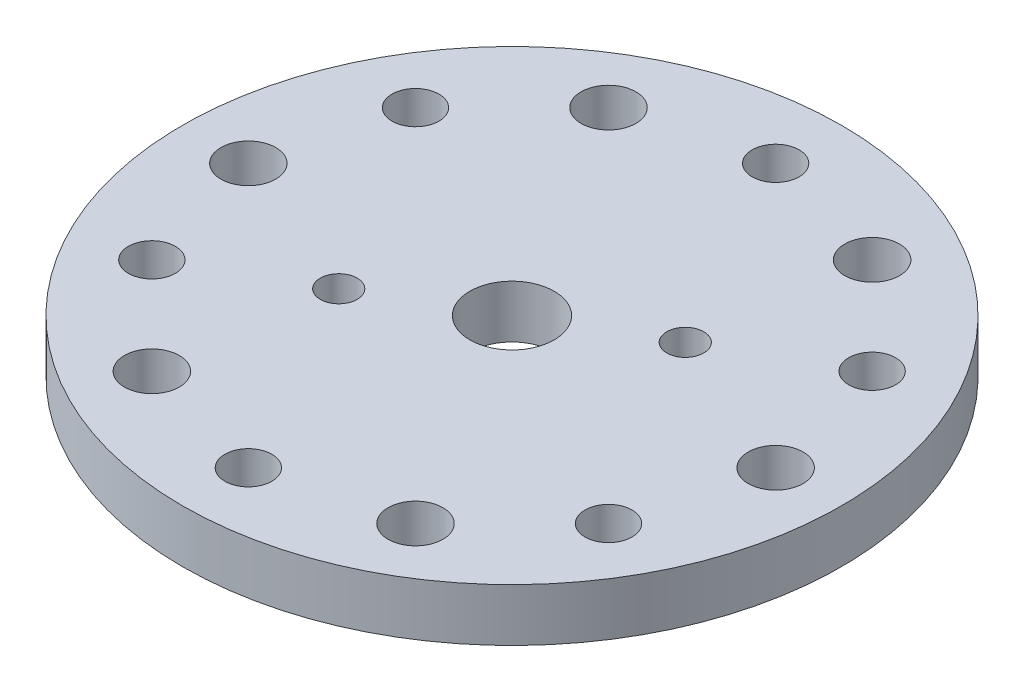
SolidWorks part; units mm, degrees
ref_plane "Front Plane" through (0, 0, 0) normal (0, 0, 1) x (1, 0, 0)
ref_plane "Top Plane" through (0, 0, 0) normal (0, 1, 0) x (1, 0, 0)
ref_plane "Right Plane" through (0, 0, 0) normal (1, 0, 0) x (0, 0, -1)
sketch "Sketch1" plane through (0, 0, 0) normal (0, 1, 0) x (1, 0, 0)
  circle A0 centre (0, 0) radius 15.875
extrude "Boss-Extrude1" add sketch "Sketch1" along normal blind 2.54
sketch "Sketch2" plane through (0, 2.54, 0) normal (0, 1, 0) x (1, 0, 0)
  circle A3 centre (0, 12.7) radius 1.5875
sketch "Sketch3" plane through (0, 2.54, 0) normal (0, 1, 0) x (1, 0, 0)
  line L1 (8.2489, -4.7625) -> (8.2489, 4.7625)
  line L2 (8.2489, 4.7625) -> (0, 9.525)
  line L3 (0, 9.525) -> (-8.2489, 4.7625)
  line L4 (-8.2489, 4.7625) -> (-8.2489, -4.7625)
  line L5 (-8.2489, -4.7625) -> (0, -9.525)
  line L6 (0, -9.525) -> (8.2489, -4.7625)
  circle A0 centre (0, 0) radius 8.2489 construction
hole_wizard "Tap Drill for #4-40 Tap1" positions "Sketch7" profile "Sketch6" hole size "#4-40" standard "ANSI Inch" end condition through all
sketch "Sketch7" plane through (0, 2.54, 0) normal (0, 1, 0) x (1, 0, 0)
  point P0 (0, 12.7)
sketch "Sketch6" plane through (0, 2.54, -12.7) normal (1, 0, 0) x (0, 0, 1)
  line L0 (0, 0) -> (0, 2.54)
  line L1 (0, 2.54) -> (1.1303, 2.54)
  line L2 (1.1303, 2.54) -> (1.1303, 0)
  line L5 (1.1303, 0) -> (0, 0)
  line L11 (0, -6.35) -> (0, 107.95) construction
  dimension "Thru Hole Dia." = 2.2606
  dimension "Thru Hole Depth" = 2.54
pattern_circular "CirPattern1" count 6 every 60 about axis through (0, 0, 0) along (0, 1, 0) of "Tap Drill for #4-40 Tap1"
sketch "Sketch8" plane through (0, 2.54, 0) normal (0, 1, 0) x (1, 0, 0)
  circle A0 centre (0, 0) radius 2.032
extrude "Cut-Extrude1" cut sketch "Sketch8" against normal blind 2.54
sketch "Sketch15" plane through (0, 2.54, 0) normal (0, 1, 0) x (1, 0, 0)
  circle A0 centre (12.7, 0) radius 1.3208
extrude "Cut-Extrude2" cut sketch "Sketch15" against normal blind 2.54
pattern_circular "CirPattern2" count 6 every 60 about axis through (0, 0, 0) along (0, 1, 0) of "Cut-Extrude2"
sketch "Sketch16" plane through (0, 2.54, 0) normal (0, 1, 0) x (1, 0, 0)
  line L0 (0, 0) -> (5.2914, 3.055)
  line L2 (0, 0) -> (-5.2914, -3.055)
hole_wizard "#2-56 Tapped Hole1" positions "Sketch26" profile "Sketch25" tap size "#2-56" standard "ANSI Inch" end condition through all
sketch "Sketch26" plane through (0, 2.54, 0) normal (0, 1, 0) x (1, 0, 0)
  point P0 (-5.2914, -3.055)
sketch "Sketch25" plane through (-5.2914, 2.54, 3.055) normal (1, 0, 0) x (0, 0, 1)
  line L0 (0, 0) -> (0, 2.54)
  line L1 (0, 2.54) -> (0.889, 2.54)
  line L2 (0.889, 2.54) -> (0.889, 0)
  line L5 (0.889, 0) -> (0, 0)
  line L11 (0, -6.35) -> (0, 107.95) construction
  dimension "Thru Tap Drill Dia." = 1.778
  dimension "Thru Tap Drill Depth" = 2.54
cosmetic thread "Hole Thread2" parameters "D2"=2.1844
hole_wizard "#2-56 Tapped Hole2" positions "Sketch28" profile "Sketch27" tap size "#2-56" standard "ANSI Inch" end condition through all
sketch "Sketch28" plane through (0, 2.54, 0) normal (0, 1, 0) x (1, 0, 0)
  point P0 (5.2914, 3.055)
sketch "Sketch27" plane through (5.2914, 2.54, -3.055) normal (1, 0, 0) x (0, 0, 1)
  line L0 (0, 0) -> (0, 2.54)
  line L1 (0, 2.54) -> (0.889, 2.54)
  line L2 (0.889, 2.54) -> (0.889, 0)
  line L5 (0.889, 0) -> (0, 0)
  line L11 (0, -6.35) -> (0, 107.95) construction
  dimension "Thru Tap Drill Dia." = 1.778
  dimension "Thru Tap Drill Depth" = 2.54
cosmetic thread "Hole Thread3" parameters "D2"=2.1844
